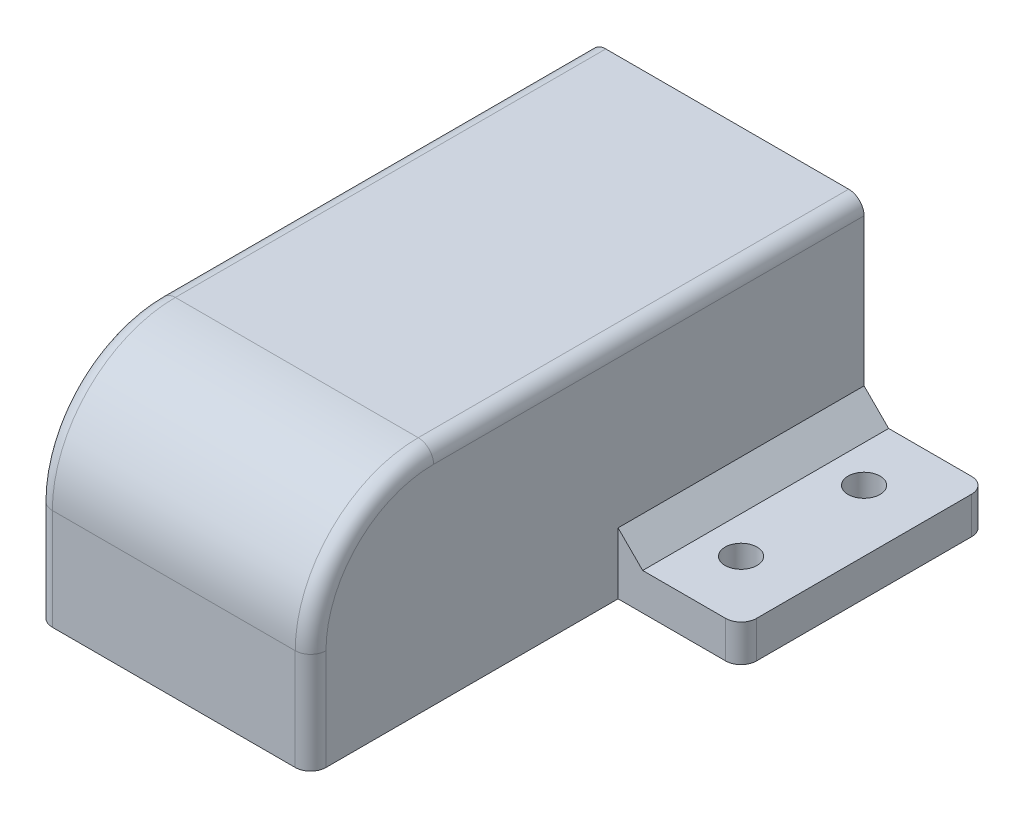
SolidWorks part; units mm, degrees
ref_plane "Спереди" through (0, 0, 0) normal (0, 0, 1) x (1, 0, 0)
ref_plane "Сверху" through (0, 0, 0) normal (0, 1, 0) x (1, 0, 0)
ref_plane "Справа" through (0, 0, 0) normal (1, 0, 0) x (0, 0, -1)
sketch "Эскиз2" plane through (0, 0, 0) normal (0, 0, 1) x (1, 0, 0)
  line L0 (-22.25, 20.2) -> (22.25, 20.2)
  line L1 (-19.25, -17.2) -> (19.25, -17.2) construction
  line L2 (-19.25, -17.2) -> (-19.25, 17.2) construction
  line L3 (-19.25, 17.2) -> (19.25, 17.2) construction
  line L4 (19.25, -17.2) -> (19.25, 17.2) construction
  line L5 (22.25, -20.2) -> (22.25, 20.2)
  line L6 (-22.25, -20.2) -> (22.25, -20.2)
  line L7 (-22.25, -20.2) -> (-22.25, 20.2)
  line L8 (19.25, -17.2) -> (-19.25, 17.2) construction
  point P9 (0, 0)
  dimension "D1" = 34.4
  dimension "D2" = 38.5
  dimension "D3" = 3
extrude "Бобышка-Вытянуть1" add sketch "Эскиз2" along normal blind 90
sketch "Эскиз1" plane through (0, 0, 0) normal (0, 0, 1) x (1, 0, 0)
  line L0 (22.25, -20.2) -> (-22.25, 20.2) construction
  line L1 (-16.9, -12.75) -> (16.9, -12.75)
  line L2 (-16.9, -12.75) -> (-16.9, 12.75)
  line L3 (-16.9, 12.75) -> (16.9, 12.75)
  line L4 (16.9, -12.75) -> (16.9, 12.75)
  line L6 (16.9, -12.75) -> (-16.9, 12.75) construction
  point P10 (0, 0)
  point P14 (0, 0)
  dimension "D1" = 25.5
  dimension "D2" = 33.8
extrude "Вырез-Вытянуть1" cut sketch "Эскиз1" along normal blind 11.5
sketch "Эскиз3" plane through (0, 0, 11.5) normal (0, 0, -1) x (-1, 0, 0)
  line L0 (-16.9, -12.75) -> (16.9, 12.75) construction
  line L5 (-18.1, -16.25) -> (18.1, 16.25) construction
  line L7 (-18.1, 16.25) -> (18.1, 16.25)
  line L8 (-18.1, 16.25) -> (-18.1, -16.25)
  line L9 (-18.1, -16.25) -> (18.1, -16.25)
  line L10 (18.1, 16.25) -> (18.1, -16.25)
  point P2 (0, 0)
  point P3 (0, 0)
  point P6 (-37.35, 0.95)
  point P11 (-1.15, 33.45)
  point P14 (-37.35, 33.45)
  dimension "D1" = 32.5
  dimension "D2" = 36.2
  dimension "D4" = 32.5
  dimension "D5" = 36.2
extrude "Вырез-Вытянуть2" cut sketch "Эскиз3" against normal blind 28.2
sketch "Эскиз4" plane through (0, 0, 39.7) normal (0, 0, -1) x (-1, 0, 0)
  line L0 (-19.35, -17.3) -> (19.35, 17.3) construction
  line L5 (-18.1, -16.25) -> (18.1, 16.25) construction
  line L6 (-18.1, 16.25) -> (-18.1, -16.25) construction
  line L7 (-19.35, 17.3) -> (19.35, 17.3)
  line L8 (-19.35, 17.3) -> (-19.35, -17.3)
  line L9 (-19.35, -17.3) -> (19.35, -17.3)
  line L10 (19.35, 17.3) -> (19.35, -17.3)
  line L11 (-18.1, -16.25) -> (18.1, -16.25) construction
  line L12 (18.1, 16.25) -> (-18.1, 16.25) construction
  line L13 (18.1, -16.25) -> (18.1, 16.25) construction
  point P10 (0, 0)
  point P11 (0, 0)
  dimension "D4" = 34.6
  dimension "D5" = 38.7
extrude "Вырез-Вытянуть3" cut sketch "Эскиз4" against normal blind 21.8
sketch "Эскиз5" plane through (0, 0, 61.5) normal (0, 0, -1) x (-1, 0, 0)
  line L0 (-19.35, -17.3) -> (19.35, 17.3) construction
  line L1 (19.35, 17.3) -> (-19.35, 17.3) construction
  line L2 (19.35, -17.3) -> (19.35, 17.3) construction
  line L3 (-7.5, 0) -> (-7.5, -17.3)
  line L4 (-19.35, -17.3) -> (19.35, -17.3) construction
  line L5 (-7.5, -17.3) -> (7.5, -17.3)
  line L6 (7.5, -17.3) -> (7.5, 0)
  arc A0 (7.5, 0) -> (-7.5, 0) centre (0, 0) ccw
  point P12 (0, 0)
  dimension "D1" = 15
extrude "Вырез-Вытянуть4" cut sketch "Эскиз5" against normal blind 3
sketch "Эскиз7" plane through (0, -20.2, 0) normal (0, -1, 0) x (1, 0, 0)
  line L4 (-22.25, 0) -> (22.25, 0)
  line L5 (22.25, 0) -> (22.25, 90)
  line L6 (22.25, 90) -> (-22.25, 90)
  line L7 (-22.25, 90) -> (-22.25, 0)
  line L8 (-22.25, 0) -> (22.25, 0)
  line L9 (22.25, 0) -> (22.25, 90)
  line L10 (22.25, 90) -> (-22.25, 90)
  line L11 (-22.25, 90) -> (-22.25, 0)
  dimension "D1" = 0
extrude "Вырез-Вытянуть6" cut sketch "Эскиз7" against normal up to surface (3.95 mm away) up to face at (0, -16.25, 25.6)
sketch "Эскиз6" plane through (22.25, 0, 0) normal (1, 0, 0) x (0, 0, -1)
  line L1 (-67, 17.2) -> (-64.5, 17.2)
  line L2 (-87, -2.8) -> (-87, -16.25)
  line L3 (-87, -16.25) -> (-64.5, -16.25)
  line L4 (-64.5, 17.2) -> (-64.5, -16.25)
  line L5 (-64.5, 0) -> (-64.5, 7.5) construction
  line L6 (-90, -16.25) -> (-90, 20.2) construction
  line L7 (-90, 20.2) -> (0, 20.2) construction
  line L8 (-90, -16.25) -> (0, -16.25) construction
  arc A0 (-67, 17.2) -> (-87, -2.8) centre (-67, -2.8) ccw
  dimension "D3" = 20
  dimension "D1" = 3
  dimension "D2" = 3
extrude "Вырез-Вытянуть5" cut sketch "Эскиз6" against normal offset from surface (38.5 mm away) 3 from offset 3 up to face at (-22.25, 1.975, 45) offset against normal yes
sketch "Эскиз8" plane through (0, -16.25, 0) normal (0, -1, 0) x (1, 0, 0)
  line L1 (22.25, 0) -> (42.25, 0)
  line L2 (22.25, 0) -> (22.25, 40)
  line L3 (22.25, 40) -> (42.25, 40)
  line L4 (42.25, 0) -> (42.25, 40)
  dimension "D1" = 40
  dimension "D2" = 20
extrude "Бобышка-Вытянуть2" add sketch "Эскиз8" against normal blind 6
sketch "Эскиз9" plane through (0, -10.25, 0) normal (0, 1, 0) x (1, 0, 0)
  line L0 (22.25, 0) -> (42.25, 0) construction
  line L1 (42.25, 0) -> (42.25, -40) construction
  line L2 (32.25, -10) -> (32.25, -30) construction
  circle A0 centre (32.25, -10) radius 2.6
  circle A1 centre (32.25, -30) radius 2.6
  dimension "D1" = 5.2
  dimension "D2" = 10
  dimension "D3" = 10
  dimension "D5" = 20
  dimension "D4" = 2
extrude "Вырез-Вытянуть7" cut sketch "Эскиз9" against normal through all
mirror "Зеркальное отражение1" about plane through (0, 0, 0) normal (1, 0, 0) of "Бобышка-Вытянуть2", "Вырез-Вытянуть7"
fillet "Скругление1" radius 2.5 4 edges at (-42.25, -13.25, 40) (-42.25, -13.25, 0) (42.25, -13.25, 40) (42.25, -13.25, 0)
fillet "Скругление2" radius 4.5 6 edges at (16.9, 12.75, 5.75) (18.1, 16.25, 25.6) (-18.1, 16.25, 25.6) (-16.9, 12.75, 5.75) (16.9, -12.75, 5.75) (-16.9, -12.75, 5.75)
fillet "Скругление3" radius 1.5 2 edges at (19.35, 17.3, 50.6) (-19.35, 17.3, 50.6)
fillet "Скругление4" radius 20 1 edges at (0, 20.2, 90)
fillet "Скругление5" radius 2.5 12 edges at (-22.25, -8.025, 90) (-22.25, 14.3421, 84.1421) (22.25, -8.025, 90) (22.25, 14.3421, 84.1421) (-22.25, 20.2, 35) (22.25, 20.2, 35) (19.25, 17.2, 65.75) (19.25, 11.3421, 81.1421) (19.25, -9.525, 87) (-19.25, 17.2, 65.75) (-19.25, 11.3421, 81.1421) (-19.25, -9.525, 87)
chamfer "Фаска1" distance 1 angle 45 5 edges at (19.25, -0.775, 64.5) (18.5178, 16.4678, 64.5) (0, 17.2, 64.5) (-18.5178, 16.4678, 64.5) (-19.25, -0.775, 64.5)
chamfer "Фаска2" distance 4 angle 45 2 edges at (-22.25, -10.25, 20) (22.25, -10.25, 20)
sketch "Эскиз11" plane through (0, 0, 0) normal (0, 0, -1) x (-1, 0, 0)
  line L0 (-39.75, -16.25) -> (39.75, -16.25) construction
  line L1 (-19.35, 3.75) -> (19.35, 3.75)
  line L2 (-19.35, 3.75) -> (-19.35, -16.25)
  line L3 (-19.35, -16.25) -> (19.35, -16.25)
  line L4 (19.35, 3.75) -> (19.35, -16.25)
  line L5 (-19.35, 15.8) -> (-19.35, -16.25) construction
  line L6 (19.35, -16.25) -> (19.35, 15.8) construction
  dimension "D1" = 20
surface "Поверхность-Вытянуть1" sketch "Эскиз11" parameters "D1"=40
split "Разделить2" trimming surface bodies 115 bodies to split 112 resulting bodies 118 119
